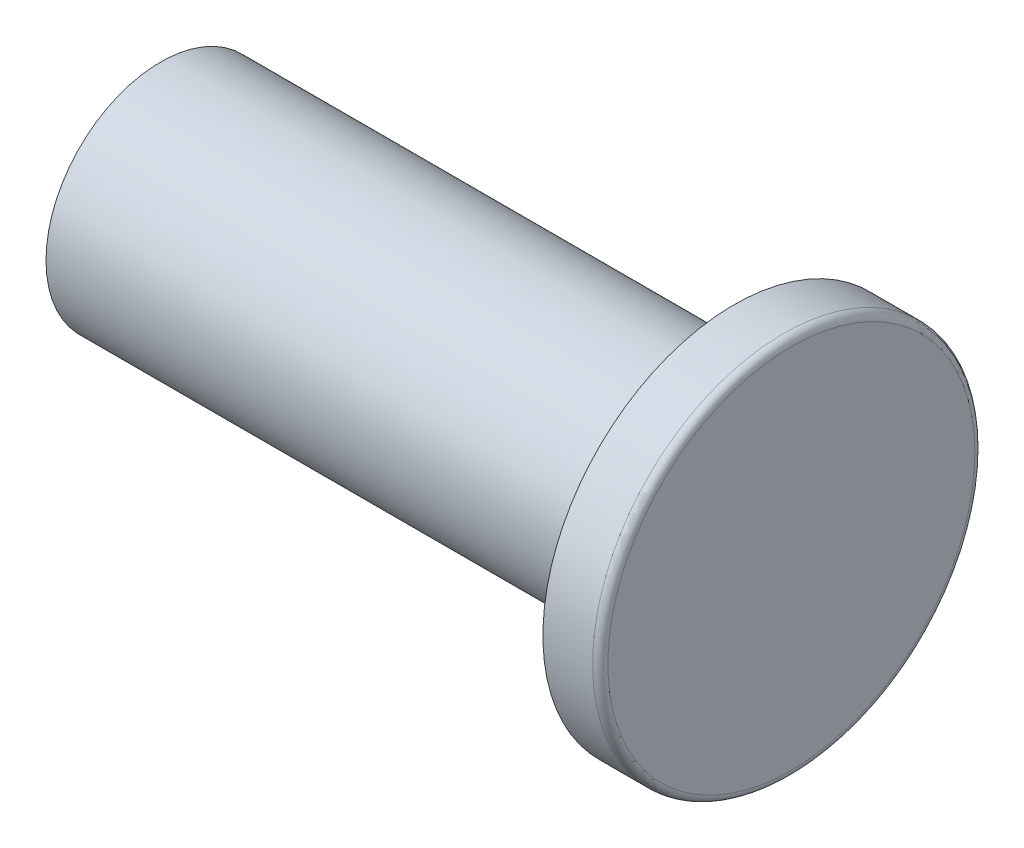
SolidWorks part; units mm, degrees
ref_plane "Front" through (0, 0, 0) normal (0, 0, 1) x (1, 0, 0)
ref_plane "Top" through (0, 0, 0) normal (0, 1, 0) x (1, 0, 0)
ref_plane "Right" through (0, 0, 0) normal (1, 0, 0) x (0, 0, -1)
sketch "Sketch1" plane through (0, 0, 0) normal (1, 0, 0) x (0, 0, -1)
  circle A0 centre (0, 0) radius 150
  dimension "D1" = 300
extrude "Boss-Extrude1" add sketch "Sketch1" along normal blind 750
sketch "Sketch2" plane through (750, 0, 0) normal (1, 0, 0) x (0, 0, -1)
  circle A0 centre (0, 0) radius 250
  dimension "D1" = 500
extrude "Boss-Extrude2" add sketch "Sketch2" along normal blind 75
fillet "Fillet1" radius 10 1 edges at (825, 0, -250)
